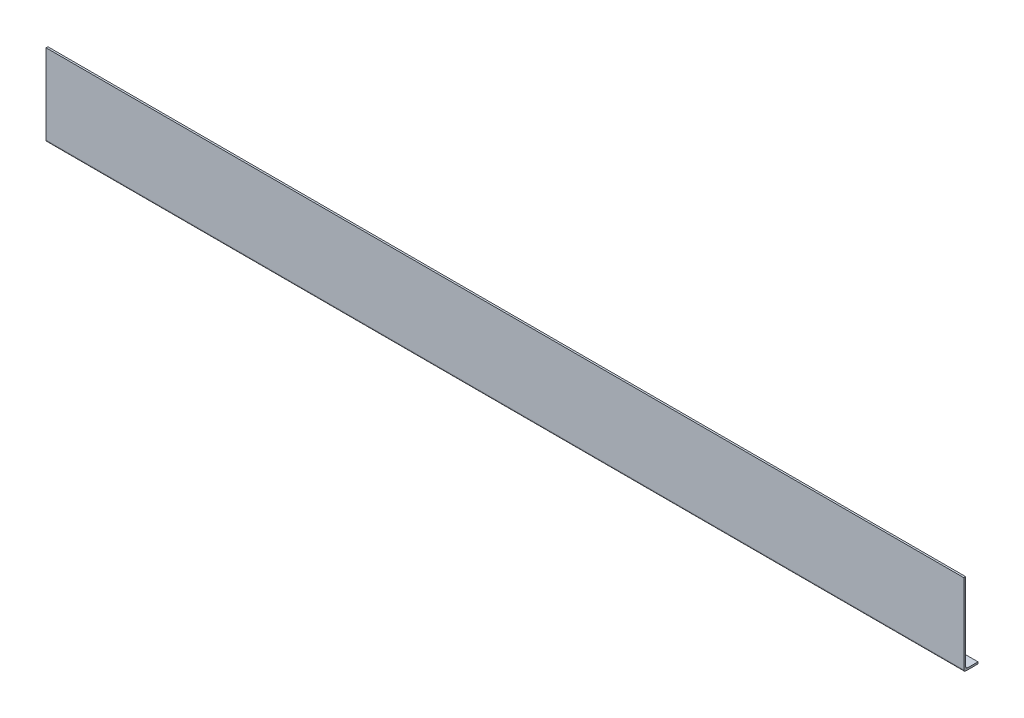
SolidWorks part; units mm, degrees
ref_plane "Front Plane" through (0, 0, 0) normal (0, 0, 1) x (1, 0, 0)
ref_plane "Top Plane" through (0, 0, 0) normal (0, 1, 0) x (1, 0, 0)
ref_plane "Right Plane" through (0, 0, 0) normal (1, 0, 0) x (0, 0, -1)
sketch "Sketch1" plane through (0, 0, 0) normal (1, 0, 0) x (0, 0, -1)
  line L0 (0, 0) -> (-23, 0)
  line L1 (-23, 0) -> (-23, 133)
  line L2 (0, 3) -> (-20, 3)
  line L3 (-20, 3) -> (-20, 133)
  line L4 (-23, 133) -> (-20, 133)
  line L5 (0, 3) -> (0, 0)
  dimension "D1" = 3
  dimension "D2" = 133
  dimension "D3" = 23
extrude "Boss-Extrude1" add sketch "Sketch1" along normal blind 1493
fillet "Fillet1" radius 3 2 edges at (746.5, 3, 20) (746.5, 0, 23)
equation "\"1Bar_Side_LB_3mm_length\"=1493.0"
equation "\"D1@Boss-Extrude1\"=\"1Bar_Side_LB_3mm_length\""
equation "\"CarBeamWidth\"=700.0"
equation "\"WheelWidth\"=650.0"
equation "\"Wheel_FrontBoxDistance\"=1390.0"
equation "\"boxLength\"=5100.0"
equation "\"boxWidth\"=1930.0"
equation "\"MetalSheet_3mm_length\"=5030.0"
equation "\"MetalSheet_3mm_width\"=1923.0"
equation "\"MetalSheet_3mm_FloorCut_L_length\"=1764.0"
equation "\"MetalSheet_3mm_FloorCut_L_disdance\"=1665.0"
equation "\"MetalSheet_3mm_FloorCut_R_length\"=1764.0"
equation "\"MetalSheet_3mm_FloorCut_R_disdance\"=1665.0"
equation "\"indoorHeight\"=1940.0"
equation "\"indoorHeight_para\"=25.0"
equation "\"rearLightHeight_para\"=265.0"
equation "\"doorColumnBar_A_FR_3mm_length_Cut\"=2310.0"
equation "\"A\"=0.0"
equation "\"haveDoor_R\"=1"
equation "\"side_door_bottom_R_3mm_length\"=1934.0"
equation "\"side_door_bottom_R_3mm_toFrontDistance\"=1583.0"
equation "\"1Bar_Side_RF_3mm_length\"=1493.0"
equation "\"1Bar_Side_RB_3mm_length\"=1493.0"
equation "\"DoorSeparator_RF_3mm_withHinge_toFrontDistance\"=1673.0"
equation "\"DoorSeparator_RF_3mm_withHinge_exist\"=1"
equation "\"DoorSeparator_RB_3mm_withHinge_toFrontDistance\"=3427.0"
equation "\"DoorSeparator_RB_3mm_withHinge_exist\"=1"
equation "\"Door_R1_L_open_Single_toFrontDistance\"=2547.5"
equation "\"Door_R1_L_open_Single_exist\"=1"
equation "\"door_base_long7_R1_L_open_Single_height\"=1890.0"
equation "\"door_base_short7_R1_L_open_Single_height\"=1890.0"
equation "\"door_base_short7_R1_L_open_Single_width\"=864"
equation "\"Door_R1_R_open_Single_toFrontDistance\"=3422.0"
equation "\"Door_R1_R_open_Single_exist\"=1"
equation "\"door_base_long7_R1_R_open_Single_height\"=1890.0"
equation "\"door_base_short7_R1_R_open_Single_height\"=1890.0"
equation "\"door_base_short7_R1_R_open_Single_width\"=864"
equation "\"x\"=66.0"
equation "\"door_base_double_BL_height\"=1890.0"
equation "\"door_base_short7_BL_Single_height\"=1890.0"
equation "\"door_base_short7_BL_Single_width\"=864"
equation "\"door_base_long7_BR_Single_height\"=1890.0"
equation "\"door_base_short7_BR_Single_height\"=1890.0"
equation "\"door_base_short7_BR_Single_width\"=864"
equation "\"da\"=62.0"
equation "\"SquareTube_length\"=1923.0"
equation "\"channelSteel_length\"=5030.0"
equation "\"SquareTube_inFront_AvgDistance\"=285.0"
equation "\"SquareTube_inFront_TotalCount\"=5"
equation "\"SquareTube_inFront1_cutDepth50_R\"=0.5"
equation "\"SquareTube_inFront1_cutDepth50_L\"=0.5"
equation "\"SquareTube_inFront2_cutDepth50_R\"=0.5"
equation "\"SquareTube_inFront2_cutDepth50_L\"=0.5"
equation "\"SquareTube_inFront3_cutDepth50_R\"=0.5"
equation "\"SquareTube_inFront3_cutDepth50_L\"=0.5"
equation "\"SquareTube_inFront4_cutDepth50_R\"=0.5"
equation "\"SquareTube_inFront4_cutDepth50_L\"=0.5"
equation "\"SquareTube_inFront5_cutDepth50_R\"=50"
equation "\"SquareTube_inFront5_cutDepth50_L\"=50"
equation "\"SquareTube_inFront6_cutDepth50_R\"=50"
equation "\"SquareTube_inFront6_cutDepth50_L\"=50"
equation "\"SquareTube_inFront7_cutDepth50_R\"=50"
equation "\"SquareTube_inFront7_cutDepth50_L\"=50"
equation "\"SquareTube_inFront8_cutDepth50_R\"=50"
equation "\"SquareTube_inFront8_cutDepth50_L\"=50"
equation "\"SquareTube_inFront9_cutDepth50_R\"=50"
equation "\"SquareTube_inFront9_cutDepth50_L\"=50"
equation "\"SquareTube_inFront10_cutDepth50_R\"=50"
equation "\"SquareTube_inFront10_cutDepth50_L\"=50"
equation "\"SquareTube_inFront11_cutDepth50_R\"=50"
equation "\"SquareTube_inFront11_cutDepth50_L\"=50"
equation "\"SquareTube_inFront12_cutDepth50_R\"=50"
equation "\"SquareTube_inFront12_cutDepth50_L\"=50"
equation "\"SquareTube_inFront13_cutDepth50_R\"=50"
equation "\"SquareTube_inFront13_cutDepth50_L\"=50"
equation "\"SquareTube_inFront14_cutDepth50_R\"=50"
equation "\"SquareTube_inFront14_cutDepth50_L\"=50"
equation "\"SquareTube_inBack_AvgDistance\"=333.125"
equation "\"SquareTube_inBack_TotalCount\"=9"
equation "\"SquareTube_inBack1_cutDepth50_R\"=50"
equation "\"SquareTube_inBack1_cutDepth50_L\"=50"
equation "\"SquareTube_inBack2_cutDepth50_R\"=50"
equation "\"SquareTube_inBack2_cutDepth50_L\"=50"
equation "\"SquareTube_inBack3_cutDepth50_R\"=50"
equation "\"SquareTube_inBack3_cutDepth50_L\"=50"
equation "\"SquareTube_inBack4_cutDepth50_R\"=50"
equation "\"SquareTube_inBack4_cutDepth50_L\"=50"
equation "\"SquareTube_inBack5_cutDepth50_R\"=50"
equation "\"SquareTube_inBack5_cutDepth50_L\"=50"
equation "\"SquareTube_inBack6_cutDepth50_R\"=0.5"
equation "\"SquareTube_inBack6_cutDepth50_L\"=0.5"
equation "\"SquareTube_inBack7_cutDepth50_R\"=0.5"
equation "\"SquareTube_inBack7_cutDepth50_L\"=0.5"
equation "\"SquareTube_inBack8_cutDepth50_R\"=0.5"
equation "\"SquareTube_inBack8_cutDepth50_L\"=0.5"
equation "\"B\"=0.0"
equation "\"haveDoor_L\"=1"
equation "\"side_door_bottom_L_3mm_length\"=1934.0"
equation "\"side_door_bottom_L_3mm_toFrontDistance\"=1583.0"
equation "\"1Bar_Side_LF_3mm_length\"=1493.0"
equation "\"DoorSeparator_LF_3mm_withHinge_toFrontDistance\"=1673.0"
equation "\"DoorSeparator_LF_3mm_withHinge_exist\"=1"
equation "\"DoorSeparator_LB_3mm_withHinge_toFrontDistance\"=3427.0"
equation "\"DoorSeparator_LB_3mm_withHinge_exist\"=1"
equation "\"Door_L1_L_open_Single_toFrontDistance\"=3422.0"
equation "\"Door_L1_L_open_Single_exist\"=1"
equation "\"door_base_long7_L1_L_open_Single_height\"=1890.0"
equation "\"door_base_short7_L1_L_open_Single_height\"=1890.0"
equation "\"door_base_short7_L1_L_open_Single_width\"=864"
equation "\"Door_L1_R_open_Single_toFrontDistance\"=2547.5"
equation "\"Door_L1_R_open_Single_exist\"=1"
equation "\"door_base_long7_L1_R_open_Single_height\"=1890.0"
equation "\"door_base_short7_L1_R_open_Single_height\"=1890.0"
equation "\"door_base_short7_L1_R_open_Single_width\"=864"
